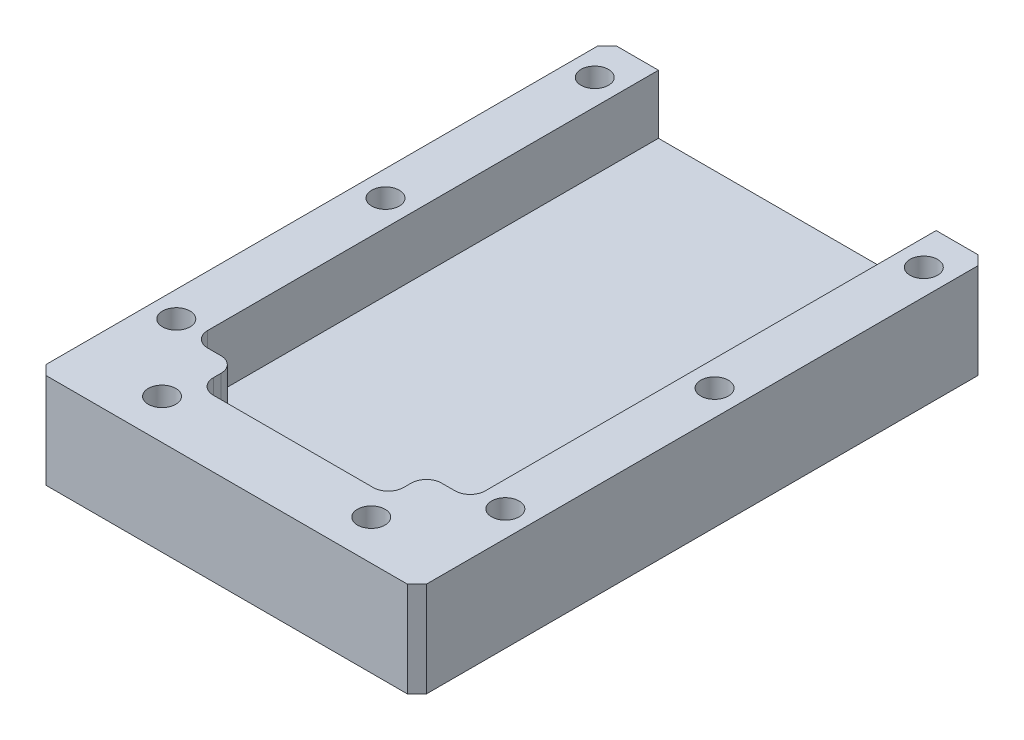
SolidWorks part; units mm, degrees
material "6061-T6 (SS)"
ref_plane "Front Plane" through (0, 0, 0) normal (0, 0, 1) x (1, 0, 0)
ref_plane "Top Plane" through (0, 0, 0) normal (0, 1, 0) x (1, 0, 0)
ref_plane "Right Plane" through (0, 0, 0) normal (1, 0, 0) x (0, 0, -1)
sketch "Sketch1" plane through (0, 0, 0) normal (0, 1, 0) x (1, 0, 0)
  line L1 (-40, 30) -> (0, 30)
  line L2 (-40, 30) -> (-40, -30)
  line L3 (-40, -30) -> (0, -30)
  line L4 (0, 30) -> (0, -30)
  point P4 (20.1288, -31.0621)
  point P5 (20.1288, 28.9379)
  point P6 (0, 0)
  dimension "D1" = 60
  dimension "D2" = 40
extrude "Boss-Extrude1" add sketch "Sketch1" along normal blind 10
sketch "Sketch2" plane through (0, 10, 0) normal (0, 1, 0) x (1, 0, 0)
  line L0 (-37.3, 26) -> (-2.7, 26)
  line L1 (-20, -30) -> (-20, -25.8) construction
  line L2 (-20, 26) -> (-20, 30) construction
  line L3 (0, 30) -> (-40, 30) construction
  line L4 (-37.3, 4) -> (-2.7, 4)
  line L5 (-37.3, -18) -> (-2.7, -18)
  line L6 (-31, -25.8) -> (-9, -25.8)
  line L7 (-40, -30) -> (0, -30) construction
  point P17 (-37.3, 26)
  point P18 (-37.3, 4)
  point P19 (-37.3, -18)
  point P20 (-31, -25.8)
  point P21 (-9, -25.8)
  point P22 (-2.7, -18)
  point P23 (-2.7, 4)
  point P24 (-2.7, 26)
  dimension "D1" = 34.6
  dimension "D2" = 4
  dimension "D4" = 7.8
  dimension "D5" = 22
  dimension "D6" = 22
  dimension "D3" = 3
hole_wizard "M2.5 Clearance Hole1" positions "Sketch2" profile "Sketch3" hole size "M2.5" standard "DIN" end condition through all
sketch "Sketch3" plane through (-37.3, 10, -26) normal (1, 0, 0) x (0, 0, 1)
  line L0 (0, 0) -> (0, 10)
  line L1 (0, 10) -> (1.45, 10)
  line L2 (1.45, 10) -> (1.45, 0)
  line L5 (1.45, 0) -> (0, 0)
  line L11 (0, -6.35) -> (0, 107.95) construction
  dimension "Thru Hole Dia." = 2.9
  dimension "Thru Hole Depth" = 10
sketch "Sketch4" plane through (0, 10, 0) normal (0, 1, 0) x (1, 0, 0)
  line L1 (0, 30) -> (-40, 30) construction
  line L3 (-34.6, 30) -> (-34.6, -19)
  line L4 (-34.6, -19) -> (-30, -19)
  line L5 (-30, -19) -> (-30, -23)
  line L6 (-30, -23) -> (-10, -23)
  line L7 (-10, -23) -> (-10, -19)
  line L8 (-10, -19) -> (-5.4, -19)
  line L9 (-5.4, -19) -> (-5.4, 30)
  line L12 (-5.4, 30) -> (-34.6, 30)
  line L13 (-20, -23) -> (-20, -30) construction
  line L14 (-40, -30) -> (0, -30) construction
  point P1 (-5.5, 30)
  point P13 (-6.2496, 30)
  point P14 (-34.5, 30)
  point P18 (-25.5, 30)
  point P19 (-26.0309, 30)
  point P20 (-33.6664, 30)
  dimension "D1" = 29.2
  dimension "D2" = 20
  dimension "D3" = 4
  dimension "D5" = 53
extrude "Cut-Extrude1" cut sketch "Sketch4" against normal blind 6.2
fillet "Fillet1" radius 1.6 6 edges at (-30, 6.9, 19) (-34.6, 6.9, 19) (-5.4, 6.9, 19) (-10, 6.9, 19) (-10, 6.9, 23) (-30, 6.9, 23)
chamfer "Chamfer1" distance 1 angle 45 4 edges at (0, 5, -30) (0, 5, 30) (-40, 5, 30) (-40, 5, -30)
